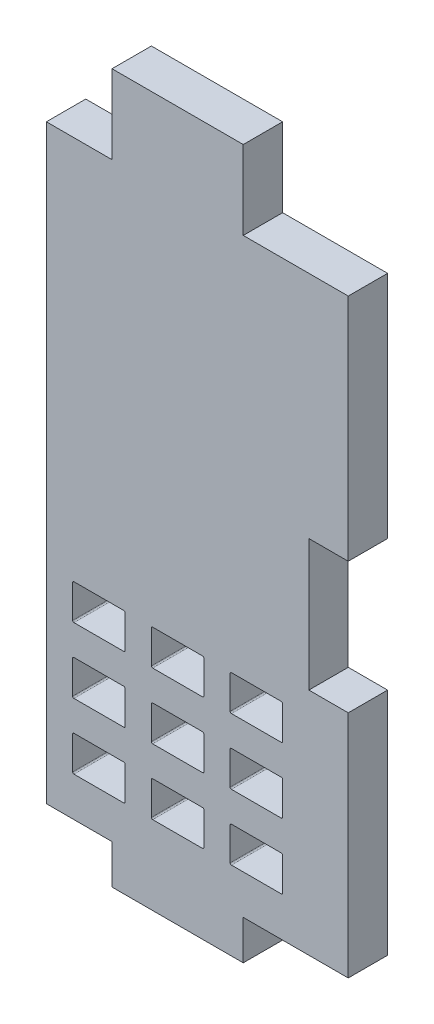
SolidWorks part; units mm, degrees
ref_plane "Front Plane" through (0, 0, 0) normal (0, 0, 1) x (1, 0, 0)
ref_plane "Top Plane" through (0, 0, 0) normal (0, 1, 0) x (1, 0, 0)
ref_plane "Right Plane" through (0, 0, 0) normal (1, 0, 0) x (0, 0, -1)
sketch "Sketch1" plane through (0, 0, 0) normal (0, 0, 1) x (1, 0, 0)
  line L0 (0, 0) -> (0, 45)
  line L1 (0, 45) -> (5, 45)
  line L2 (5, 45) -> (5, 51)
  line L3 (5, 51) -> (15, 51)
  line L4 (15, 51) -> (15, 45)
  line L5 (15, 45) -> (23, 45)
  line L6 (23, 45) -> (23, 27.5)
  line L7 (23, 27.5) -> (20, 27.5)
  line L8 (20, 27.5) -> (20, 17.5)
  line L9 (20, 17.5) -> (23, 17.5)
  line L10 (23, 17.5) -> (23, 0)
  line L11 (23, 0) -> (15, 0)
  line L12 (15, 0) -> (15, -3)
  line L13 (15, -3) -> (5, -3)
  line L14 (5, -3) -> (5, 0)
  line L15 (5, 0) -> (0, 0)
  dimension "D1" = 10
  dimension "D2" = 3
  dimension "D3" = 23
  dimension "D4" = 10
  dimension "D5" = 8
  dimension "D6" = 45
  dimension "D7" = 6
  dimension "D8" = 3
extrude "Boss-Extrude1" add sketch "Sketch1" along normal blind 3
sketch "Sketch2" plane through (0, 0, 0) normal (0, 0, -1) x (-1, 0, 0)
  line L0 (0, 0) -> (-5, 0) construction
  line L1 (-2.1, 3) -> (-5.9, 3)
  line L2 (-2, 3.1) -> (-2, 5.6)
  line L3 (-2.1, 5.7) -> (-5.9, 5.7)
  line L4 (-6, 3.1) -> (-6, 5.6)
  line L5 (0, 45) -> (0, 0) construction
  line L6 (-8.1, 3) -> (-11.9, 3)
  line L7 (-8, 3.1) -> (-8, 5.6)
  line L8 (-8.1, 5.7) -> (-11.9, 5.7)
  line L9 (-12, 3.1) -> (-12, 5.6)
  line L10 (-14.1, 3) -> (-17.9, 3)
  line L11 (-14, 3.1) -> (-14, 5.6)
  line L12 (-14.1, 5.7) -> (-17.9, 5.7)
  line L13 (-18, 3.1) -> (-18, 5.6)
  line L14 (-8.1, 8) -> (-11.9, 8)
  line L15 (-8, 8.1) -> (-8, 10.6)
  line L16 (-8.1, 10.7) -> (-11.9, 10.7)
  line L17 (-12, 8.1) -> (-12, 10.6)
  line L18 (-14.1, 8) -> (-17.9, 8)
  line L19 (-14, 8.1) -> (-14, 10.6)
  line L20 (-14.1, 10.7) -> (-17.9, 10.7)
  line L21 (-18, 8.1) -> (-18, 10.6)
  line L22 (-8.1, 13) -> (-11.9, 13)
  line L23 (-8, 13.1) -> (-8, 15.6)
  line L24 (-8.1, 15.7) -> (-11.9, 15.7)
  line L25 (-12, 13.1) -> (-12, 15.6)
  line L26 (-14.1, 13) -> (-17.9, 13)
  line L27 (-14, 13.1) -> (-14, 15.6)
  line L28 (-14.1, 15.7) -> (-17.9, 15.7)
  line L29 (-18, 13.1) -> (-18, 15.6)
  line L30 (-2.1, 8) -> (-5.9, 8)
  line L31 (-2, 8.1) -> (-2, 10.6)
  line L32 (-2.1, 10.7) -> (-5.9, 10.7)
  line L33 (-6, 8.1) -> (-6, 10.6)
  line L34 (-2.1, 13) -> (-5.9, 13)
  line L35 (-2, 13.1) -> (-2, 15.6)
  line L36 (-2.1, 15.7) -> (-5.9, 15.7)
  line L37 (-6, 13.1) -> (-6, 15.6)
  arc A0 (-2, 5.6) -> (-2.1, 5.7) centre (-2.1, 5.6) ccw
  arc A1 (-5.9, 5.7) -> (-6, 5.6) centre (-5.9, 5.6) ccw
  arc A2 (-5.9, 3) -> (-6, 3.1) centre (-5.9, 3.1) cw
  arc A3 (-2.1, 3) -> (-2, 3.1) centre (-2.1, 3.1) ccw
  arc A4 (-8.1, 3) -> (-8, 3.1) centre (-8.1, 3.1) ccw
  arc A5 (-11.9, 3) -> (-12, 3.1) centre (-11.9, 3.1) cw
  arc A6 (-11.9, 5.7) -> (-12, 5.6) centre (-11.9, 5.6) ccw
  arc A7 (-8, 5.6) -> (-8.1, 5.7) centre (-8.1, 5.6) ccw
  arc A8 (-14.1, 3) -> (-14, 3.1) centre (-14.1, 3.1) ccw
  arc A9 (-17.9, 3) -> (-18, 3.1) centre (-17.9, 3.1) cw
  arc A10 (-17.9, 5.7) -> (-18, 5.6) centre (-17.9, 5.6) ccw
  arc A11 (-14, 5.6) -> (-14.1, 5.7) centre (-14.1, 5.6) ccw
  arc A12 (-8.1, 8) -> (-8, 8.1) centre (-8.1, 8.1) ccw
  arc A13 (-11.9, 8) -> (-12, 8.1) centre (-11.9, 8.1) cw
  arc A14 (-11.9, 10.7) -> (-12, 10.6) centre (-11.9, 10.6) ccw
  arc A15 (-8, 10.6) -> (-8.1, 10.7) centre (-8.1, 10.6) ccw
  arc A16 (-14.1, 8) -> (-14, 8.1) centre (-14.1, 8.1) ccw
  arc A17 (-17.9, 8) -> (-18, 8.1) centre (-17.9, 8.1) cw
  arc A18 (-17.9, 10.7) -> (-18, 10.6) centre (-17.9, 10.6) ccw
  arc A19 (-14, 10.6) -> (-14.1, 10.7) centre (-14.1, 10.6) ccw
  arc A20 (-8.1, 13) -> (-8, 13.1) centre (-8.1, 13.1) ccw
  arc A21 (-11.9, 13) -> (-12, 13.1) centre (-11.9, 13.1) cw
  arc A22 (-11.9, 15.7) -> (-12, 15.6) centre (-11.9, 15.6) ccw
  arc A23 (-8, 15.6) -> (-8.1, 15.7) centre (-8.1, 15.6) ccw
  arc A24 (-14.1, 13) -> (-14, 13.1) centre (-14.1, 13.1) ccw
  arc A25 (-17.9, 13) -> (-18, 13.1) centre (-17.9, 13.1) cw
  arc A26 (-17.9, 15.7) -> (-18, 15.6) centre (-17.9, 15.6) ccw
  arc A27 (-14, 15.6) -> (-14.1, 15.7) centre (-14.1, 15.6) ccw
  arc A28 (-2.1, 8) -> (-2, 8.1) centre (-2.1, 8.1) ccw
  arc A29 (-5.9, 8) -> (-6, 8.1) centre (-5.9, 8.1) cw
  arc A30 (-5.9, 10.7) -> (-6, 10.6) centre (-5.9, 10.6) ccw
  arc A31 (-2, 10.6) -> (-2.1, 10.7) centre (-2.1, 10.6) ccw
  arc A32 (-2.1, 13) -> (-2, 13.1) centre (-2.1, 13.1) ccw
  arc A33 (-5.9, 13) -> (-6, 13.1) centre (-5.9, 13.1) cw
  arc A34 (-5.9, 15.7) -> (-6, 15.6) centre (-5.9, 15.6) ccw
  arc A35 (-2, 15.6) -> (-2.1, 15.7) centre (-2.1, 15.6) ccw
  point P10 (-2, 5.7)
  point P13 (-6, 5.7)
  point P16 (-6, 3)
  point P19 (-16, 5.7)
  dimension "D5" = 0.1
  dimension "D1" = 2.7
  dimension "D2" = 4
  dimension "D3" = 3
  dimension "D4" = 2
  dimension "D8" = 2.3
  dimension "D9" = 2
  dimension "D6" = 3
  dimension "D7" = 3
extrude "Cut-Extrude1" cut sketch "Sketch2" against normal through all
